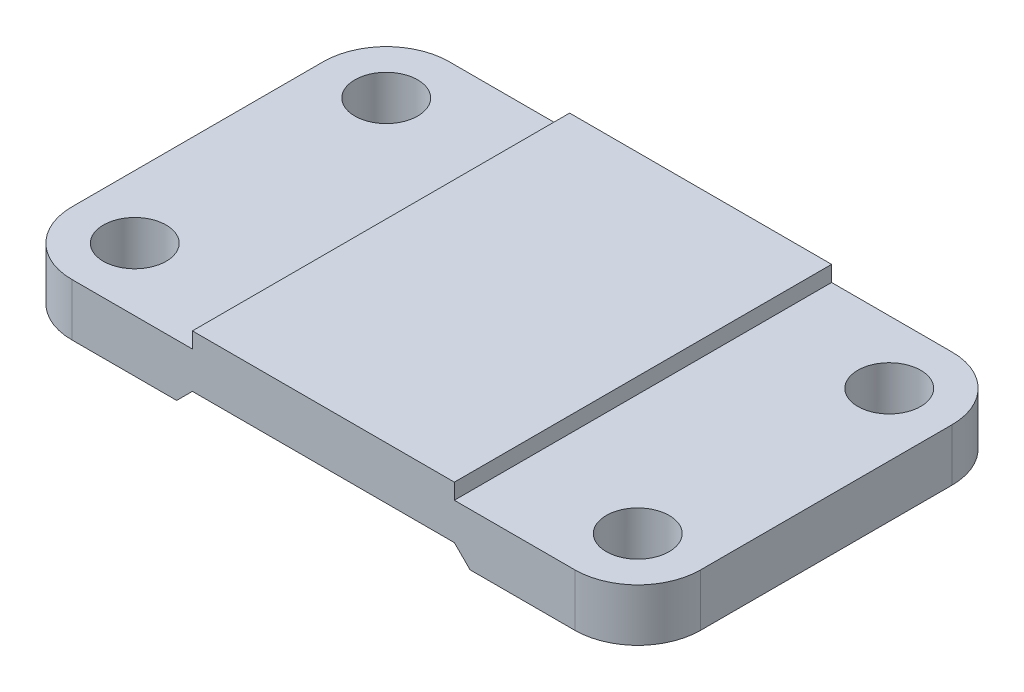
SolidWorks part; units mm, degrees
ref_plane "Front Plane" through (0, 0, 0) normal (0, 0, 1) x (1, 0, 0)
ref_plane "Top Plane" through (0, 0, 0) normal (0, 1, 0) x (1, 0, 0)
ref_plane "Right Plane" through (0, 0, 0) normal (1, 0, 0) x (0, 0, -1)
sketch "Sketch1" plane through (0, 0, 0) normal (0, 0, 1) x (1, 0, 0)
  line L0 (0, 0) -> (0, 10)
  line L1 (0, 10) -> (35, 10)
  line L5 (85, 10) -> (120, 10)
  line L6 (120, 10) -> (120, 0)
  line L7 (120, 0) -> (88, 0)
  line L8 (88, 0) -> (85, 3)
  line L9 (85, 3) -> (35, 3)
  line L10 (35, 3) -> (32, 0)
  line L11 (32, 0) -> (0, 0)
  line L12 (35, 10) -> (35, 13)
  line L13 (35, 13) -> (85, 13)
  line L14 (85, 13) -> (85, 10)
  point P5 (86.8447, 3.2788)
  point P14 (0, 0)
  point P15 (85, 3.6341)
  point P16 (35, 3.8117)
  point P17 (85, 3.4564)
  point P18 (35, 3.6341)
  point P19 (85, 4.3446)
  point P20 (0, 0)
  point P21 (0, 0)
  point P22 (0, 0)
  dimension "D1" = 10
  dimension "D2" = 3
  dimension "D3" = 3
  dimension "D4" = 35
  dimension "D5" = 120
  dimension "D6" = 56
extrude "Boss-Extrude1" add sketch "Sketch1" along normal blind 72
sketch "Sketch2" plane through (0, 10, 0) normal (0, 1, 0) x (1, 0, 0)
  line L0 (60, 0) -> (60, -72) construction
  line L2 (12, 0) -> (108, 0)
  line L3 (0, -12) -> (0, -60)
  line L4 (12, -72) -> (108, -72)
  line L5 (120, -12) -> (120, -60)
  line L6 (0, 0) -> (120, 0)
  line L7 (0, 0) -> (0, -72)
  line L8 (0, -72) -> (120, -72)
  line L9 (120, 0) -> (120, -72)
  arc A0 (108, -72) -> (120, -60) centre (108, -60) ccw
  arc A1 (0, -60) -> (12, -72) centre (12, -60) ccw
  arc A2 (12, 0) -> (0, -12) centre (12, -12) ccw
  arc A3 (108, 0) -> (120, -12) centre (108, -12) cw
  circle A4 centre (12, -12) radius 6
  circle A5 centre (108, -12) radius 6
  circle A6 centre (108, -60) radius 6
  circle A7 centre (12, -60) radius 6
  point P8 (120, -72)
  point P15 (0, 0)
  line M10 (35, 0) -> (0, 0)
  line M11 (0, 0) -> (0, -72)
  line M12 (0, -72) -> (35, -72)
  dimension "D1" = 12
  dimension "D2" = 12
  dimension "D3" = 12
  dimension "D4" = 12
  dimension "D5" = 12
  dimension "D6" = 12
extrude "Cut-Extrude1" cut sketch "Sketch2" against normal blind 72 contours A2 M10 M11 | L6 A3 L9 | A0 L8 L9 | A6 | A5 | A7 | A4 | A1 M11 M12
